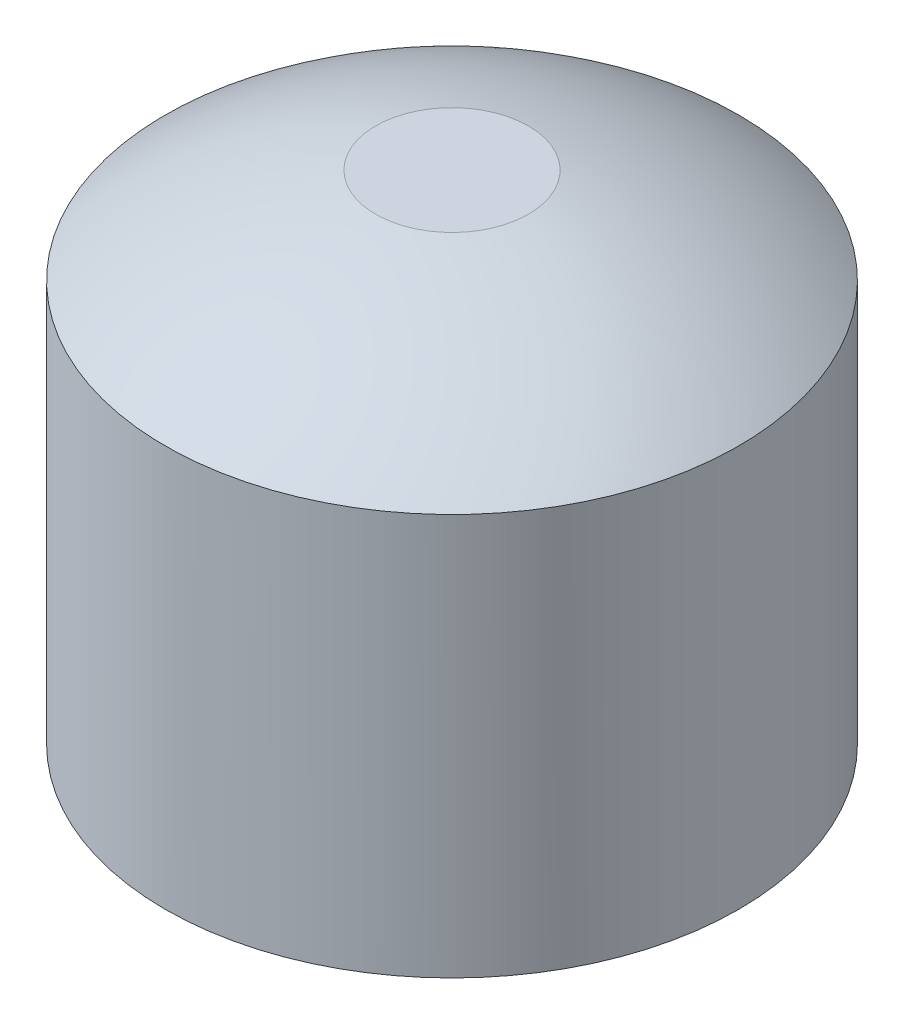
SolidWorks part; units mm, degrees
ref_plane "Front Plane" through (0, 0, 0) normal (0, 0, 1) x (1, 0, 0)
ref_plane "Top Plane" through (0, 0, 0) normal (0, 1, 0) x (1, 0, 0)
ref_plane "Right Plane" through (0, 0, 0) normal (1, 0, 0) x (0, 0, -1)
sketch "Sketch1" plane through (0, 0, 0) normal (0, 1, 0) x (1, 0, 0)
  circle A0 centre (0, 0) radius 75
  circle A1 centre (0, 0) radius 70
  dimension "D1" = 150
  dimension "D2" = 140
extrude "Boss-Extrude1" add sketch "Sketch1" along normal blind 100
sketch "Sketch3" plane through (0, 0, 0) normal (1, 0, 0) x (0, 0, -1)
  line L0 (70, 100) -> (-70, 100) construction
  line L1 (70, 100) -> (-70, 100) construction
  line L2 (-70, 100) -> (-75, 100)
  line L3 (-75, 100) -> (-75, 105)
  line L5 (0, -20.1549) -> (0, 315.4905) construction
  line L10 (0, 130) -> (-20, 130)
  line L11 (-75, 105) -> (-70, 100) construction
  line L12 (0, 130) -> (0, 122.9289)
  line L13 (0, 122.9289) -> (-20, 122.9289)
  line L14 (-20, 130) -> (-20, 122.9289) construction
  line L15 (-63.5, 112.85) -> (-63.5, 105) construction
  line L16 (-63.5, 105) -> (-75, 105) construction
  spline S0 degree 2 poles (-20, 130) (-50.6672, 123.4774) (-75, 105) knots 0 0 0 1 1 1
  spline S1 degree 2 poles (-20, 122.9289) (-48.6445, 117.781) (-70, 100) knots 0 0 0 1 1 1
  dimension "D4" = 11.5
  dimension "D3" = 30
  dimension "D1" = 20
  dimension "D2" = 5
  dimension "D5" = 7.85
revolve "Revolve1" add sketch "Sketch3" angle 360 about L5
